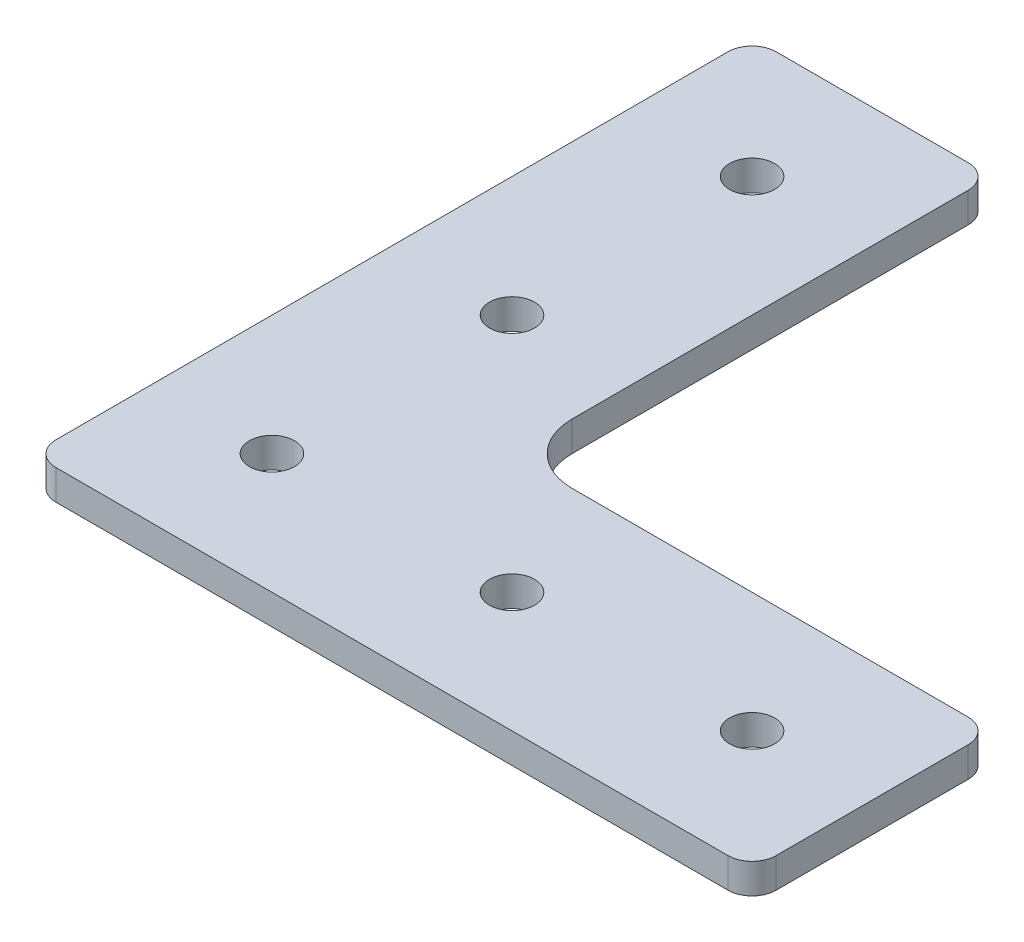
SolidWorks part; units mm, degrees
ref_plane "Front Plane" through (0, 0, 0) normal (0, 0, 1) x (1, 0, 0)
ref_plane "Top Plane" through (0, 0, 0) normal (0, 1, 0) x (1, 0, 0)
ref_plane "Right Plane" through (0, 0, 0) normal (1, 0, 0) x (0, 0, -1)
sketch "Sketch1" plane through (0, 0, 0) normal (0, 1, 0) x (1, 0, 0)
  line L1 (-10.16, -38.1) -> (6.35, -38.1)
  line L2 (-12.7, -35.56) -> (-12.7, 35.56)
  line L3 (-10.16, 38.1) -> (10.16, 38.1)
  line L4 (12.7, -6.35) -> (12.7, 35.56)
  line L7 (6.35, -38.1) -> (60.96, -38.1)
  line L9 (19.05, -12.7) -> (60.96, -12.7)
  line L10 (63.5, -35.56) -> (63.5, -15.24)
  circle A0 centre (0, -25.4) radius 2.3813
  circle A1 centre (0, 0) radius 2.3813
  circle A2 centre (0, 25.4) radius 2.3813
  circle A3 centre (25.4, -25.4) radius 2.3813
  circle A4 centre (50.8, -25.4) radius 2.3812
  arc A5 (19.05, -12.7) -> (12.7, -6.35) centre (19.05, -6.35) cw
  arc A6 (12.7, 35.56) -> (10.16, 38.1) centre (10.16, 35.56) ccw
  arc A7 (-12.7, 35.56) -> (-10.16, 38.1) centre (-10.16, 35.56) cw
  arc A8 (-12.7, -35.56) -> (-10.16, -38.1) centre (-10.16, -35.56) ccw
  arc A9 (60.96, -38.1) -> (63.5, -35.56) centre (60.96, -35.56) ccw
  arc A10 (63.5, -15.24) -> (60.96, -12.7) centre (60.96, -15.24) ccw
  point P0 (0, 0)
  point P23 (12.7, 38.1)
  point P26 (-12.7, 38.1)
  point P29 (-12.7, -38.1)
  point P32 (63.5, -38.1)
  point P35 (63.5, -12.7)
  point P36 (0, 0)
  dimension "D5" = 4.7625
  dimension "D6" = 4.7625
  dimension "D7" = 4.7625
  dimension "D8" = 4.7625
  dimension "D9" = 4.7625
  dimension "D14" = 6.35
  dimension "D15" = 2.54
  dimension "D1" = 76.2
  dimension "D2" = 25.4
  dimension "D3" = 57.15
  dimension "D4" = 25.4
  dimension "D10" = 25.4
  dimension "D11" = 25.4
  dimension "D12" = 25.4
  dimension "D13" = 25.4
  dimension "D16" = 12.7
extrude "Boss-Extrude1" add sketch "Sketch1" along normal blind 3.175
